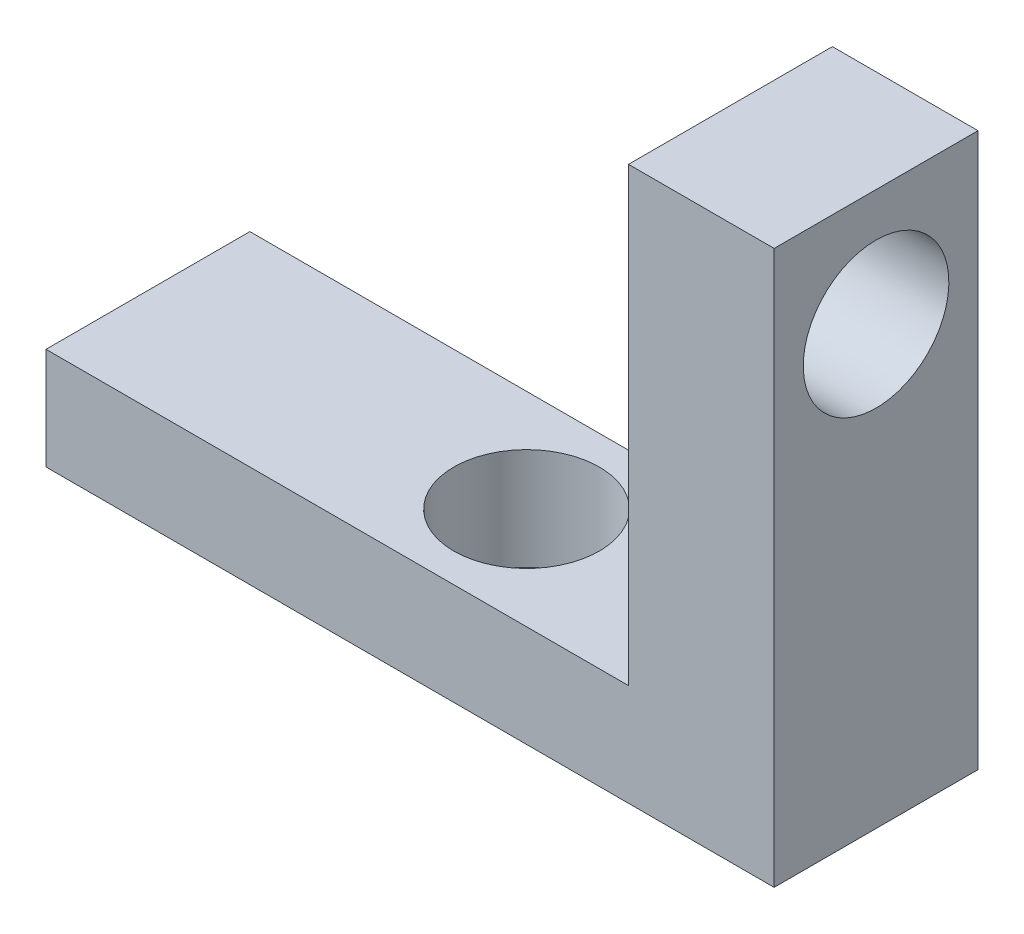
SolidWorks part; units mm, degrees
ref_plane "Front Plane" through (0, 0, 0) normal (0, 0, 1) x (1, 0, 0)
ref_plane "Top Plane" through (0, 0, 0) normal (0, 1, 0) x (1, 0, 0)
ref_plane "Right Plane" through (0, 0, 0) normal (1, 0, 0) x (0, 0, -1)
sketch "Sketch1" plane through (0, 0, 0) normal (0, 0, 1) x (1, 0, 0)
  line L1 (-12.5, 9.5) -> (12.5, 9.5)
  line L2 (-12.5, 9.5) -> (-12.5, -9.5)
  line L3 (-12.5, -9.5) -> (12.5, -9.5)
  line L4 (12.5, 9.5) -> (12.5, -9.5)
  line L5 (-12.5, 9.5) -> (12.5, -9.5) construction
  line L6 (-12.5, -9.5) -> (12.5, 9.5) construction
  point P0 (0, 0)
  dimension "D1" = 19
  dimension "D2" = 25
extrude "Boss-Extrude1" add sketch "Sketch1" along normal blind 7
sketch "Sketch2" plane through (0, 0, 7) normal (0, 0, 1) x (1, 0, 0)
  line L1 (-12.5, 9.5) -> (7.5, 9.5)
  line L2 (-12.5, 9.5) -> (-12.5, -6)
  line L3 (-12.5, -6) -> (7.5, -6)
  line L4 (7.5, 9.5) -> (7.5, -6)
  dimension "D1" = 15.5
  dimension "D2" = 20
extrude "Cut-Extrude1" cut sketch "Sketch2" against normal blind 7
sketch "Sketch4" plane through (0, -6, 0) normal (0, 1, 0) x (1, 0, 0)
  line L0 (-10.45, 0) -> (10.45, 0) construction
  line L1 (-12.5, 0) -> (-12.5, -7) construction
  circle A0 centre (0.5, -3.5) radius 2.5
  dimension "D2" = 5
  dimension "D1" = 3.5
  dimension "D3" = 13
extrude "Cut-Extrude3" cut sketch "Sketch4" against normal through all
sketch "Sketch5" plane through (12.5, 0, 0) normal (1, 0, 0) x (0, 0, -1)
  line L0 (-7, 9.5) -> (0, 9.5) construction
  line L1 (-7, -9.5) -> (-7, 9.5) construction
  circle A0 centre (-3.5, 5.5) radius 2.5
  dimension "D3" = 5
  dimension "D1" = 4
  dimension "D2" = 3.5
extrude "Cut-Extrude4" cut sketch "Sketch5" against normal blind 10
